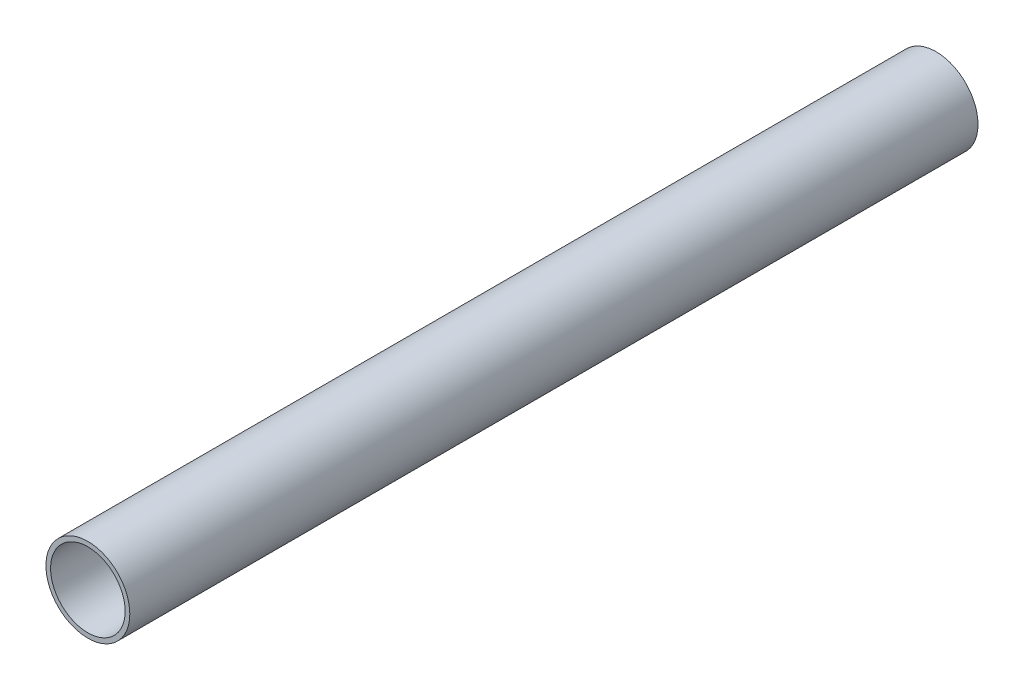
SolidWorks part; units mm, degrees
ref_plane "Alzado" through (0, 0, 0) normal (0, 0, 1) x (1, 0, 0)
ref_plane "Planta" through (0, 0, 0) normal (0, 1, 0) x (1, 0, 0)
ref_plane "Vista lateral" through (0, 0, 0) normal (1, 0, 0) x (0, 0, -1)
sketch "Croquis1" plane through (0, 0, 0) normal (0, 0, 1) x (1, 0, 0)
  circle A0 centre (0, 0) radius 8
  circle A1 centre (0, 0) radius 9
  dimension "D2" = 18
  dimension "D1" = 1
extrude "Saliente-Extruir1" add sketch "Croquis1" along normal mid plane 182
